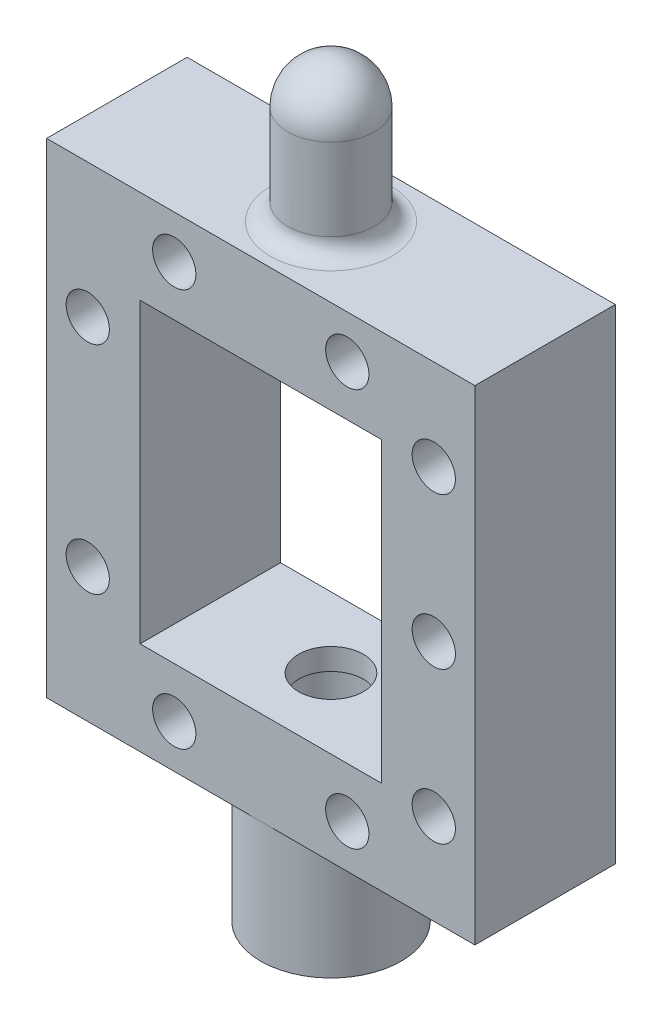
SolidWorks part; units mm, degrees
ref_plane "Front Plane" through (0, 0, 0) normal (0, 0, 1) x (1, 0, 0)
ref_plane "Top Plane" through (0, 0, 0) normal (0, 1, 0) x (1, 0, 0)
ref_plane "Right Plane" through (0, 0, 0) normal (1, 0, 0) x (0, 0, -1)
sketch "Sketch1" plane through (0, 0, 0) normal (0, 0, 1) x (1, 0, 0)
  line L1 (-31.4325, 35.56) -> (31.4325, 35.56)
  line L2 (-31.4325, 35.56) -> (-31.4325, -35.56)
  line L3 (-31.4325, -35.56) -> (31.4325, -35.56)
  line L4 (31.4325, 35.56) -> (31.4325, -35.56)
  line L5 (-31.4325, 35.56) -> (31.4325, -35.56) construction
  line L6 (-31.4325, -35.56) -> (31.4325, 35.56) construction
  point P0 (0, 0)
extrude "Boss-Extrude1" add sketch "Sketch1" along normal blind 20.6248
sketch "Sketch2" plane through (0, 0, 20.6248) normal (0, 0, 1) x (1, 0, 0)
  line L1 (-17.7165, 21.844) -> (17.7165, 21.844)
  line L2 (-17.7165, 21.844) -> (-17.7165, -21.844)
  line L3 (-17.7165, -21.844) -> (17.7165, -21.844)
  line L4 (17.7165, 21.844) -> (17.7165, -21.844)
  line L5 (-17.7165, 21.844) -> (17.7165, -21.844) construction
  line L6 (-17.7165, -21.844) -> (17.7165, 21.844) construction
  point P0 (0, 0)
sketch "Sketch4" plane through (0, 0, 20.6248) normal (0, 0, 1) x (1, 0, 0)
  line L0 (0, 45.008) -> (0, -53.1778) construction
  line L1 (-53.0293, 0) -> (61.4961, 0) construction
  circle A0 centre (-12.7, 29.21) radius 3.175
  circle A1 centre (-25.4, 15.875) radius 3.175
  circle A2 centre (-12.7, -29.21) radius 3.175
  circle A3 centre (-25.4, -15.875) radius 3.175
  circle A4 centre (12.7, -29.21) radius 3.175
  circle A5 centre (12.7, 29.21) radius 3.175
  circle A6 centre (25.4, 0) radius 3.175
  circle A7 centre (25.4, 22.225) radius 3.175
  circle A8 centre (25.4, -22.225) radius 3.175
  dimension "D1" = 12.7
  dimension "D3" = 6.35
  dimension "D5" = 6.35
  dimension "D7" = 25.4
  dimension "D8" = 22.225
  dimension "D2" = 29.21
  dimension "D4" = 15.875
  dimension "D6" = 25.4
  dimension "D9" = 25.4
extrude "Cut-Extrude2" cut sketch "Sketch4" against normal through all both and the other way through all
sketch "Sketch5" plane through (0, 0, 0) normal (1, 0, 0) x (0, 0, -1)
  line L0 (-16.6624, 35.56) -> (-16.6624, 50.1199)
  line L1 (-20.6248, 35.56) -> (0, 35.56) construction
  line L2 (-10.3124, 35.56) -> (-10.3124, 56.5724) construction
  line L4 (-16.6624, 35.56) -> (-10.3124, 35.56)
  line L5 (-10.3124, 56.4699) -> (-10.3124, 35.56)
  arc A0 (-16.6624, 50.1199) -> (-10.3124, 56.4699) centre (-10.3124, 50.1199) cw
  point P9 (-14.8025, 54.61)
  dimension "D1" = 12.7
  dimension "D2" = 6.35
  dimension "D3" = 19.05
revolve "Revolve2" add sketch "Sketch5" angle 360 about L2
fillet "Fillet1" radius 2.54 1 edges at (0, 35.56, 3.9624)
extrude "Cut-Extrude3" cut sketch "Sketch2" against normal through all
sketch "Sketch6" plane through (0, 21.844, 0) normal (0, -1, 0) x (1, 0, 0)
  line L0 (-31.4325, 0) -> (31.4325, 0) construction
  circle A0 centre (0, 10.3124) radius 2.7686
  dimension "D1" = 10.3124
extrude "Cut-Extrude4" cut sketch "Sketch6" against normal blind 27.94
sketch "Sketch7" plane through (0, -35.56, 0) normal (0, -1, 0) x (1, 0, 0)
  line L0 (-31.4325, 0) -> (31.4325, 0) construction
  circle A0 centre (0, 10.3124) radius 10.3124
  dimension "D1" = 10.3124
extrude "Boss-Extrude2" add sketch "Sketch7" along normal blind 17.78
sketch "Sketch8" plane through (0, -53.34, 0) normal (0, -1, 0) x (1, 0, 0)
  line L1 (-7.3996, 3.1297) -> (-5.7954, 3.1297)
  line L2 (-5.7954, 3.1297) -> (7.3996, 3.1297)
  circle A2 centre (0, 10.3124) radius 10.3124 construction
  arc A3 (-7.3996, 3.1297) -> (7.3996, 3.1297) centre (0, 10.3124) ccw
extrude "Cut-Extrude5" cut sketch "Sketch8" against normal blind 17.78 contours L1 L2 A3
sketch "Sketch9" plane through (0, -21.844, 0) normal (0, 1, 0) x (1, 0, 0)
  line L0 (31.4325, -20.6248) -> (-31.4325, -20.6248) construction
  circle A0 centre (0, -10.3124) radius 4.7625
  dimension "D1" = 9.525
  dimension "D2" = 10.3124
extrude "Cut-Extrude6" cut sketch "Sketch9" against normal blind 3.175
hole_wizard "1/2-20 Tapped Hole1" positions "Sketch10" profile "Sketch11" tap size "1/2-20" standard "ANSI Inch"
sketch "Sketch10" plane through (0, -53.34, 0) normal (0, -1, 0) x (-1, 0, 0)
  point P0 (0, -10.3124)
sketch "Sketch11" plane through (0, -53.34, 10.3124) normal (1, 0, 0) x (0, 0, -1)
  line L0 (0, 0) -> (0, 28.321)
  line L1 (0, 28.321) -> (5.7544, 28.321)
  line L2 (5.7544, 28.321) -> (5.7544, 0)
  line L5 (5.7544, 0) -> (0, 0)
  line L11 (0, -6.35) -> (0, 107.95) construction
  dimension "Thru Tap Drill Dia." = 11.5087
  dimension "Thru Tap Drill Depth" = 28.321
cosmetic thread "Hole Thread1" parameters "D2"=12.7
